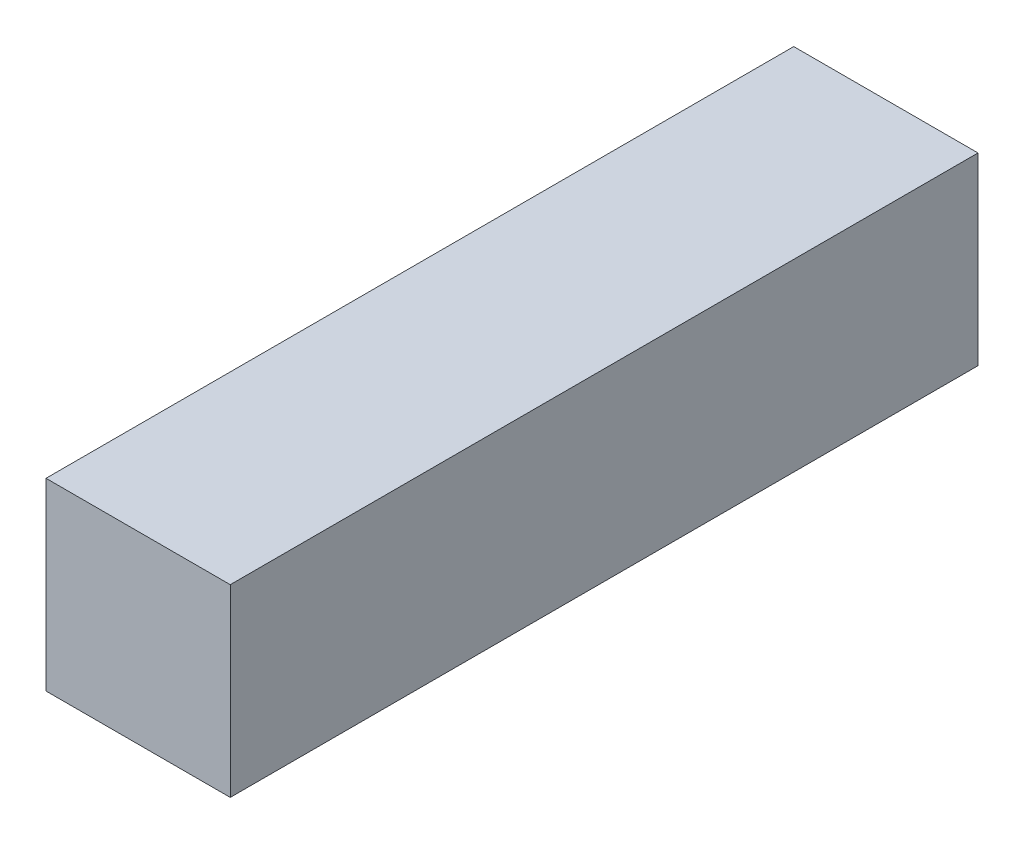
SolidWorks part; units mm, degrees
ref_plane "Front Plane" through (0, 0, 0) normal (0, 0, 1) x (1, 0, 0)
ref_plane "Top Plane" through (0, 0, 0) normal (0, 1, 0) x (1, 0, 0)
ref_plane "Right Plane" through (0, 0, 0) normal (1, 0, 0) x (0, 0, -1)
sketch "Sketch1" plane through (0, 0, 0) normal (0, 0, 1) x (1, 0, 0)
  line L1 (-6.35, -6.35) -> (6.35, -6.35)
  line L2 (-6.35, -6.35) -> (-6.35, 6.35)
  line L3 (-6.35, 6.35) -> (6.35, 6.35)
  line L4 (6.35, -6.35) -> (6.35, 6.35)
  line L5 (-6.35, -6.35) -> (6.35, 6.35) construction
  line L6 (-6.35, 6.35) -> (6.35, -6.35) construction
  point P0 (0, 0)
  dimension "D1" = 12.7
  dimension "D2" = 12.7
extrude "Boss-Extrude1" add sketch "Sketch1" along normal blind 51.5391
